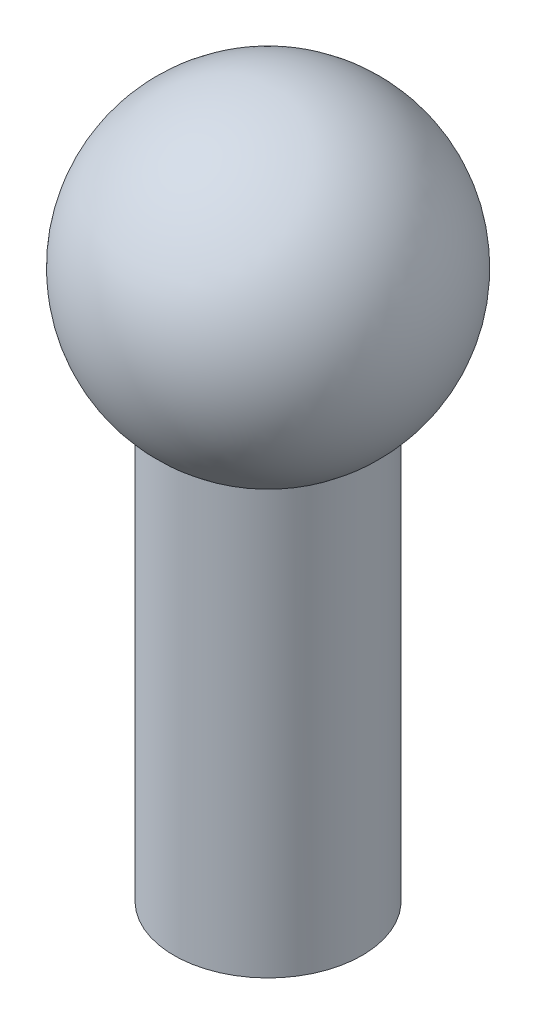
SolidWorks part; units mm, degrees
ref_plane "Front Plane" through (0, 0, 0) normal (0, 0, 1) x (1, 0, 0)
ref_plane "Top Plane" through (0, 0, 0) normal (0, 1, 0) x (1, 0, 0)
ref_plane "Right Plane" through (0, 0, 0) normal (1, 0, 0) x (0, 0, -1)
sketch "Sketch1" plane through (0, 0, 0) normal (0, 0, 1) x (1, 0, 0)
  line L0 (0, 0) -> (-12, 0)
  line L1 (-12, 0) -> (-12, 54)
  line L16 (0, 0) -> (0, 90)
  arc A0 (0, 90) -> (-12, 54) centre (0, 70) ccw
  dimension "D1" = 40
  dimension "D2" = 90
  dimension "D3" = 12
revolve "Revolve1" add sketch "Sketch1" angle 360 about L16
sketch "Sketch2" plane through (0, 0, 0) normal (0, -1, 0) x (-1, 0, 0)
  circle A0 centre (0, 0) radius 10
  circle A1 centre (0, -22) radius 5
  circle A2 centre (0, 22) radius 5
  dimension "D1" = 20
  dimension "D3" = 10
  dimension "D4" = 10
  dimension "D2" = 22
  dimension "D5" = 22
extrude "Cut-Extrude1" cut sketch "Sketch2" against normal blind 30
